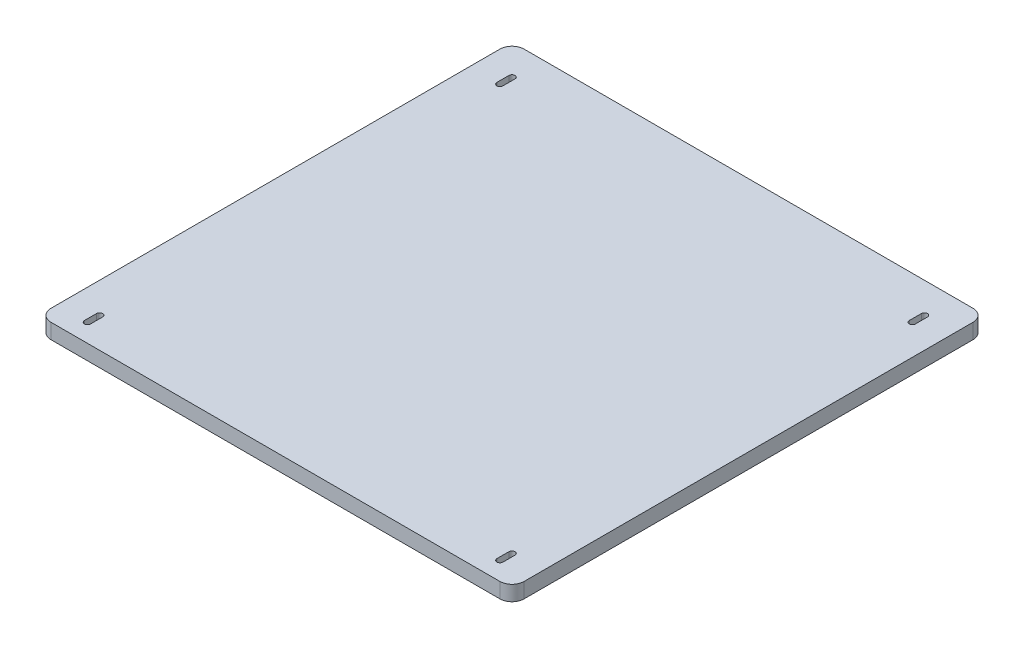
SolidWorks part; units mm, degrees
ref_plane "Front Plane" through (0, 0, 0) normal (0, 0, 1) x (1, 0, 0)
ref_plane "Top Plane" through (0, 0, 0) normal (0, 1, 0) x (1, 0, 0)
ref_plane "Right Plane" through (0, 0, 0) normal (1, 0, 0) x (0, 0, -1)
sketch "Sketch1" plane through (0, 0, 0) normal (0, 1, 0) x (1, 0, 0)
  line L0 (46.517, 0) -> (-82.2994, 0) construction
  line L1 (-188.341, 198.501) -> (188.341, 198.501)
  line L2 (-198.501, 188.341) -> (-198.501, -188.341)
  line L3 (-188.341, -198.501) -> (188.341, -198.501)
  line L4 (198.501, 188.341) -> (198.501, -188.341)
  line L5 (-198.501, 198.501) -> (198.501, -198.501) construction
  line L6 (-198.501, -198.501) -> (198.501, 198.501) construction
  line L7 (-173.0375, 173.0375) -> (173.0375, 173.0375) construction
  line L8 (-173.0375, 173.0375) -> (-173.0375, -173.0375) construction
  line L9 (-173.0375, -173.0375) -> (173.0375, -173.0375) construction
  line L10 (173.0375, 173.0375) -> (173.0375, -173.0375) construction
  line L11 (-173.0375, 173.0375) -> (173.0375, -173.0375) construction
  line L12 (-173.0375, -173.0375) -> (173.0375, 173.0375) construction
  line L13 (0, 124.5673) -> (0, -111.5962) construction
  line L14 (-173.0375, 173.0375) -> (-173.0375, 162.8775) construction
  line L15 (-170.4975, 173.0375) -> (-170.4975, 162.8775)
  line L16 (-175.5775, 173.0375) -> (-175.5775, 162.8775)
  line L17 (173.0375, 173.0375) -> (173.0375, 162.8775) construction
  line L18 (175.5775, 173.0375) -> (175.5775, 162.8775)
  line L19 (170.4975, 173.0375) -> (170.4975, 162.8775)
  line L20 (-173.0375, -173.0375) -> (-173.0375, -183.1975) construction
  line L21 (-170.4975, -173.0375) -> (-170.4975, -183.1975)
  line L22 (-175.5775, -173.0375) -> (-175.5775, -183.1975)
  line L23 (173.0375, -173.0375) -> (173.0375, -183.1975) construction
  line L24 (175.5775, -173.0375) -> (175.5775, -183.1975)
  line L25 (170.4975, -173.0375) -> (170.4975, -183.1975)
  arc A0 (188.341, 198.501) -> (198.501, 188.341) centre (188.341, 188.341) cw
  arc A1 (188.341, -198.501) -> (198.501, -188.341) centre (188.341, -188.341) ccw
  arc A2 (-198.501, -188.341) -> (-188.341, -198.501) centre (-188.341, -188.341) ccw
  arc A3 (-188.341, 198.501) -> (-198.501, 188.341) centre (-188.341, 188.341) ccw
  arc A4 (175.5775, 173.0375) -> (170.4975, 173.0375) centre (173.0375, 173.0375) ccw
  arc A5 (170.4975, 162.8775) -> (175.5775, 162.8775) centre (173.0375, 162.8775) ccw
  arc A6 (-170.4975, -173.0375) -> (-175.5775, -173.0375) centre (-173.0375, -173.0375) ccw
  arc A7 (-175.5775, -183.1975) -> (-170.4975, -183.1975) centre (-173.0375, -183.1975) ccw
  arc A8 (-170.4975, 173.0375) -> (-175.5775, 173.0375) centre (-173.0375, 173.0375) ccw
  arc A9 (-175.5775, 162.8775) -> (-170.4975, 162.8775) centre (-173.0375, 162.8775) ccw
  arc A10 (175.5775, -173.0375) -> (170.4975, -173.0375) centre (173.0375, -173.0375) ccw
  arc A11 (170.4975, -183.1975) -> (175.5775, -183.1975) centre (173.0375, -183.1975) ccw
  point P0 (0, 0)
  point P18 (0, 0)
  point P23 (173.0375, 167.9575)
  point P31 (-173.0375, 167.9575)
  point P39 (-173.0375, -178.1175)
  point P45 (173.0375, -178.1175)
  dimension "D2" = 10.16
  dimension "D5" = 2.54
  dimension "D6" = 10.16
  dimension "D1" = 397.002
  dimension "D3" = 346.075
  dimension "D4" = 346.075
extrude "Boss-Extrude1" add sketch "Sketch1" along normal blind 12.7
